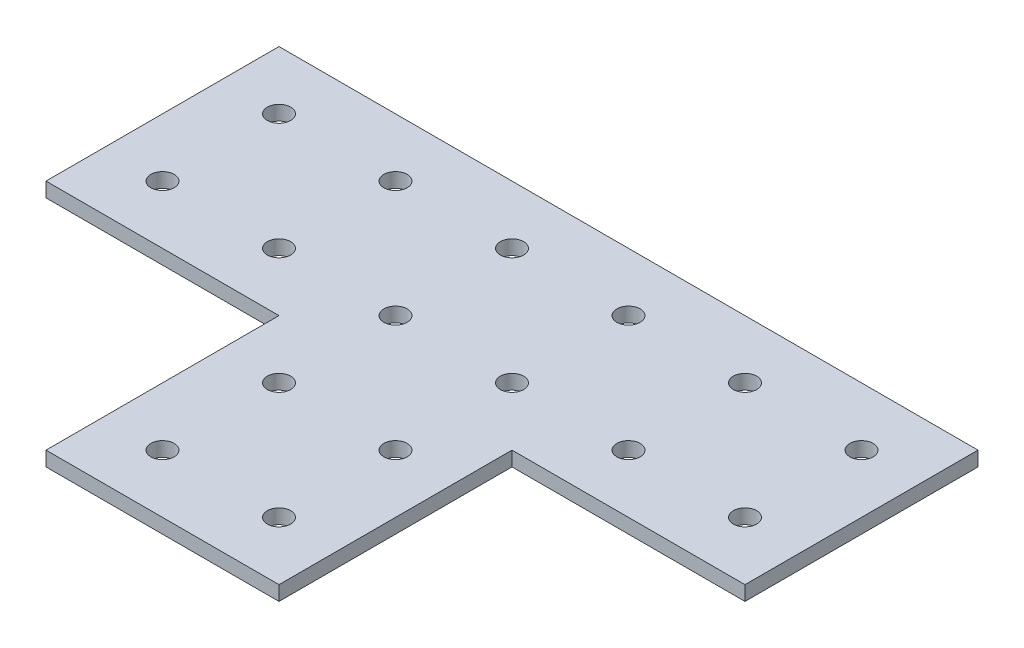
SolidWorks part; units mm, degrees
ref_plane "Front Plane" through (0, 0, 0) normal (0, 0, 1) x (1, 0, 0)
ref_plane "Top Plane" through (0, 0, 0) normal (0, 1, 0) x (1, 0, 0)
ref_plane "Right Plane" through (0, 0, 0) normal (1, 0, 0) x (0, 0, -1)
sketch "Sketch1" plane through (0, 0, 0) normal (0, 1, 0) x (1, 0, 0)
  line L0 (25.4, -25.4) -> (76.2, -25.4)
  line L1 (-76.2, -25.4) -> (-25.4, -25.4)
  line L2 (-76.2, -25.4) -> (-76.2, 25.4)
  line L3 (-76.2, 25.4) -> (76.2, 25.4)
  line L4 (76.2, -25.4) -> (76.2, 25.4)
  line L5 (-76.2, -25.4) -> (76.2, 25.4) construction
  line L6 (-76.2, 25.4) -> (76.2, -25.4) construction
  line L8 (-25.4, -25.4) -> (-25.4, -76.2)
  line L9 (-25.4, -76.2) -> (25.4, -76.2)
  line L10 (25.4, -25.4) -> (25.4, -76.2)
  point P0 (0, 0)
  dimension "D3" = 50.8
  dimension "D1" = 152.4
  dimension "D2" = 50.8
  dimension "D4" = 50.8
  dimension "D5" = 50.8
extrude "Boss-Extrude1" add sketch "Sketch1" along normal blind 3.175
sketch "Sketch2" plane through (0, 3.175, 0) normal (0, 1, 0) x (1, 0, 0)
  line L0 (76.2, 25.4) -> (-76.2, 25.4) construction
  line L1 (-76.2, 25.4) -> (-76.2, -25.4) construction
  circle A0 centre (-63.5, 12.7) radius 2.54
  point P6 (-72.7774, 2.2545)
  point P7 (0, 0)
  dimension "D1" = 12.7
  dimension "D2" = 12.7
extrude "Cut-Extrude1" cut sketch "Sketch2" against normal up to surface (3.175 mm away) up to face at (0, 0, 25.4)
pattern_linear "LPattern1" count 6 spacing 25.4 along (1, 0, 0) count 2 spacing 25.4 along (0, 0, 1) of "Cut-Extrude1"
sketch "Sketch3" plane through (0, 3.175, 0) normal (0, 1, 0) x (1, 0, 0)
  line L0 (-25.4, -76.2) -> (25.4, -76.2) construction
  circle A0 centre (-12.7, -63.5) radius 2.54
  dimension "D1" = 12.7
extrude "Cut-Extrude2" cut sketch "Sketch3" against normal up to surface (3.175 mm away) up to face at (-38.1, 0, -15.24)
pattern_linear "LPattern2" count 2 spacing 25.4 along (1, 0, 0) count 2 spacing 25.4 along (0, 0, -1) of "Cut-Extrude2"
